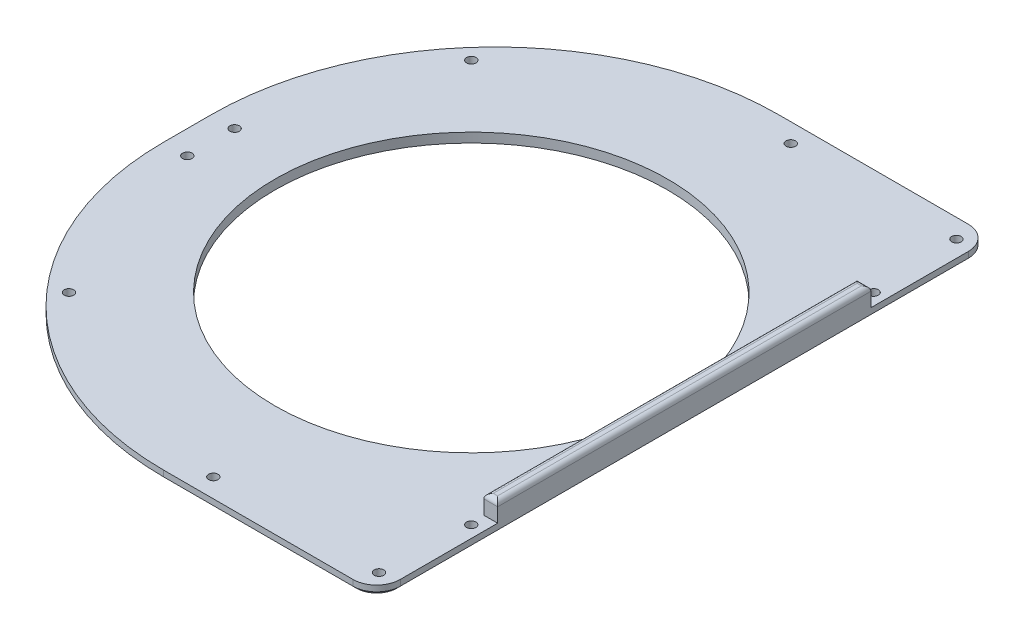
SolidWorks part; units mm, degrees
ref_plane "Спереди" through (0, 0, 0) normal (0, 0, 1) x (1, 0, 0)
ref_plane "Сверху" through (0, 0, 0) normal (0, 1, 0) x (1, 0, 0)
ref_plane "Справа" through (0, 0, 0) normal (1, 0, 0) x (0, 0, -1)
sketch "Эскиз1" plane through (0, 0, 0) normal (0, 1, 0) x (1, 0, 0)
  line L1 (-120, -130) -> (120, -130)
  line L2 (-120, -130) -> (-120, 130)
  line L3 (-120, 130) -> (120, 130)
  line L4 (120, -130) -> (120, 130)
  line L5 (0, 130) -> (0, -130) construction
  line L6 (-120, 0) -> (120, 0) construction
  point P0 (0, 0)
  dimension "D1" = 240
  dimension "D2" = 260
extrude "Бобышка-Вытянуть1" add sketch "Эскиз1" along normal blind 4
sketch "Эскиз2" plane through (0, 4, 0) normal (0, 1, 0) x (1, 0, 0)
  line L0 (0, 138.6532) -> (0, 0) construction
  line L1 (0, 0) -> (-210.918, 0) construction
  line L3 (13, 72) -> (83, 72) construction
  line L4 (13, 72) -> (13, 122) construction
  line L5 (13, 122) -> (83, 122) construction
  line L6 (83, 72) -> (83, 122) construction
  line L7 (48, 122) -> (48, 72) construction
  line L8 (13, 97) -> (83, 97) construction
  line L9 (-130, -10) -> (-110, -10) construction
  line L10 (-130, -10) -> (-130, 10) construction
  line L11 (-130, 10) -> (-110, 10) construction
  line L12 (-110, -10) -> (-110, 10) construction
  line L13 (-120, 10) -> (-120, -10) construction
  line L14 (-130, 0) -> (-110, 0) construction
  line L15 (-85, -85) -> (85, -85) construction
  line L16 (-85, -85) -> (-85, 85) construction
  line L17 (-85, 85) -> (85, 85) construction
  line L18 (85, -85) -> (85, 85) construction
  line L19 (0, 85) -> (0, -85) construction
  line L20 (-85, 0) -> (85, 0) construction
  circle A0 centre (83, 122) radius 2
  circle A1 centre (13, 122) radius 2
  circle A2 centre (83, -122) radius 2
  circle A3 centre (13, -122) radius 2
  circle A4 centre (-110, 10) radius 2
  circle A5 centre (-110, -10) radius 2
  circle A6 centre (-85, 85) radius 2
  circle A7 centre (85, 85) radius 2
  circle A8 centre (-85, -85) radius 2
  circle A9 centre (85, -85) radius 2
  point P4 (48, 97)
  point P15 (-120, 0)
  dimension "D5" = 20
  dimension "D8" = 170
  dimension "D1" = 50
  dimension "D2" = 70
  dimension "D3" = 13
  dimension "D4" = 72
  dimension "D6" = 20
  dimension "D7" = 110
extrude "Вырез-Вытянуть1" cut sketch "Эскиз2" against normal through all
sketch "Эскиз3" plane through (0, 4, 0) normal (0, 1, 0) x (1, 0, 0)
  line L0 (-120, -130) -> (120, -130) construction
  line L1 (120, 130) -> (90, 130)
  line L2 (120, 130) -> (120, -130)
  line L3 (120, -130) -> (90, -130)
  line L4 (90, 130) -> (90, -130)
  dimension "D1" = 30
extrude "Вырез-Вытянуть2" cut sketch "Эскиз3" against normal blind 6
fillet "Скругление2" radius 10 2 edges at (90, 2, -130) (90, 2, 130)
fillet "Скругление3" radius 120 2 edges at (-120, 2, -130) (-120, 2, 130)
sketch "Эскиз4" plane through (0, 4, 0) normal (0, 1, 0) x (1, 0, 0)
  circle A0 centre (0, 0) radius 83
  dimension "D1" = 166
extrude "Вырез-Вытянуть3" cut sketch "Эскиз4" against normal blind 6
sketch "Эскиз5" plane through (0, 4, 0) normal (0, 1, 0) x (1, 0, 0)
  line L0 (90, 120) -> (90, -120) construction
  line L1 (84.1572, -78.8649) -> (90, -78.8649)
  line L2 (84.1572, -78.8649) -> (84.1572, 78.8649)
  line L3 (84.1572, 78.8649) -> (90, 78.8649)
  line L4 (90, -78.8649) -> (90, 78.8649)
  line L5 (87.0786, 78.8649) -> (87.0786, -78.8649) construction
  line L6 (84.1572, 0) -> (90, 0) construction
  point P0 (87.0786, 0)
extrude "Бобышка-Вытянуть2" add sketch "Эскиз5" along normal blind 8
fillet "Скругление4" radius 2 4 edges at (87.0786, 12, 78.8649) (84.1572, 12, 0) (87.0786, 12, -78.8649) (90, 12, 0)
chamfer "Фаска1" distance 1.5 angle 45 8 edges at (-120, 0, 0) (-84.8528, 0, 94.8528) (-84.8528, 0, -94.8528) (40, 0, 130) (40, 0, -130) (87.0711, 0, 127.0711) (87.0711, 0, -127.0711) (90, 0, 0)
